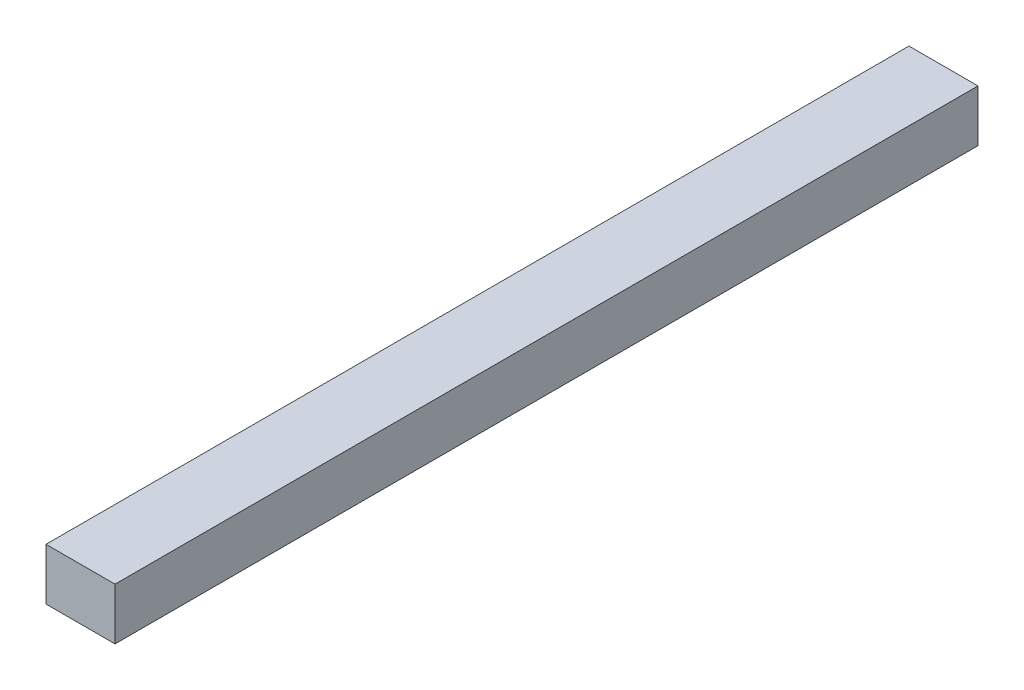
SolidWorks part; units mm, degrees
ref_plane "前视基准面" through (0, 0, 0) normal (0, 0, 1) x (1, 0, 0)
ref_plane "上视基准面" through (0, 0, 0) normal (0, 1, 0) x (1, 0, 0)
ref_plane "右视基准面" through (0, 0, 0) normal (1, 0, 0) x (0, 0, -1)
sketch "草图1" plane through (0, 0, 0) normal (0, 0, 1) x (1, 0, 0)
  line L1 (-200, 150) -> (200, 150)
  line L2 (-200, 150) -> (-200, -150)
  line L3 (-200, -150) -> (200, -150)
  line L4 (200, 150) -> (200, -150)
  line L5 (-200, 150) -> (200, -150) construction
  line L6 (-200, -150) -> (200, 150) construction
  point P1 (0, 0)
  dimension "D1" = 400
  dimension "D2" = 300
extrude "凸台-拉伸1" add sketch "草图1" along normal mid plane 5000
